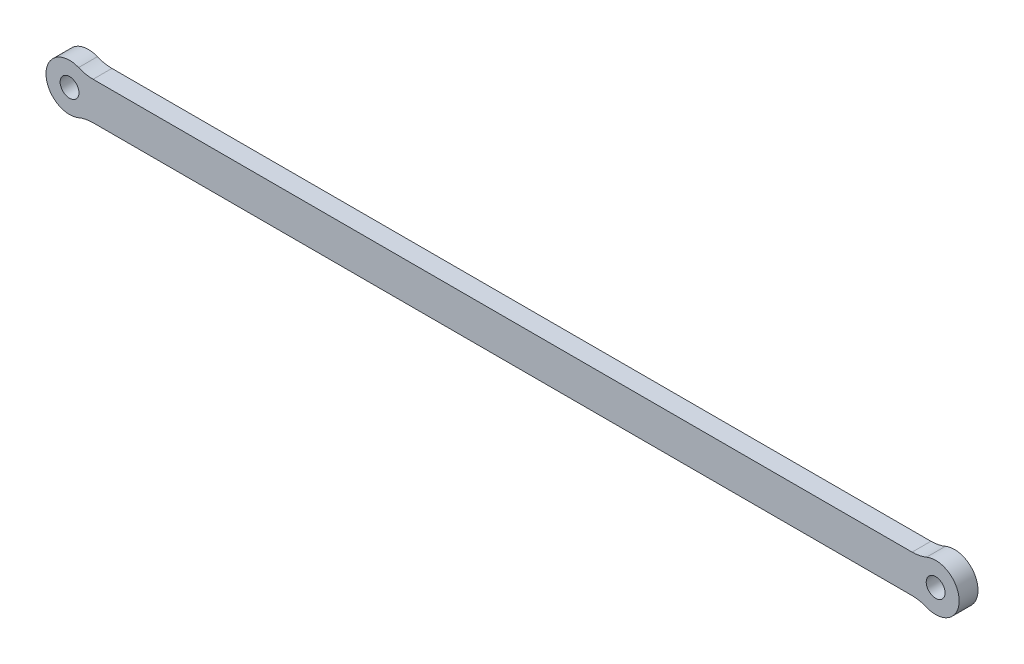
SolidWorks part; units mm, degrees
ref_plane "Ebene vorne" through (0, 0, 0) normal (0, 0, 1) x (1, 0, 0)
ref_plane "Ebene oben" through (0, 0, 0) normal (0, 1, 0) x (1, 0, 0)
ref_plane "Ebene rechts" through (0, 0, 0) normal (1, 0, 0) x (0, 0, -1)
sketch "Skizze1" plane through (0, 0, 0) normal (0, 0, 1) x (1, 0, 0)
  line L0 (-115, 0) -> (115, 0) construction
  line L1 (-108.75, 5) -> (108.75, 5)
  line L2 (-108.75, -5) -> (108.75, -5)
  line L4 (0, 5) -> (0, -5) construction
  circle A2 centre (-115, 0) radius 2.5
  arc A4 (-112.5962, 5.7692) -> (-112.5962, -5.7692) centre (-115, 0) ccw
  arc A5 (-108.75, -5) -> (-112.5962, -5.7692) centre (-108.75, -15) ccw
  arc A6 (-108.75, 5) -> (-112.5962, 5.7692) centre (-108.75, 15) cw
  arc A7 (108.75, 5) -> (112.5962, 5.7692) centre (108.75, 15) ccw
  arc A8 (108.75, -5) -> (112.5962, -5.7692) centre (108.75, -15) cw
  arc A9 (112.5962, 5.7692) -> (112.5962, -5.7692) centre (115, 0) cw
  circle A10 centre (115, 0) radius 2.5
  point P2 (0, 0)
  point P15 (0, 0)
  dimension "D3" = 5
  dimension "D4" = 12.5
  dimension "D5" = 10
  dimension "D1" = 10
  dimension "D2" = 115
extrude "Aufsatz-Linear austragen1" add sketch "Skizze1" along normal blind 5
